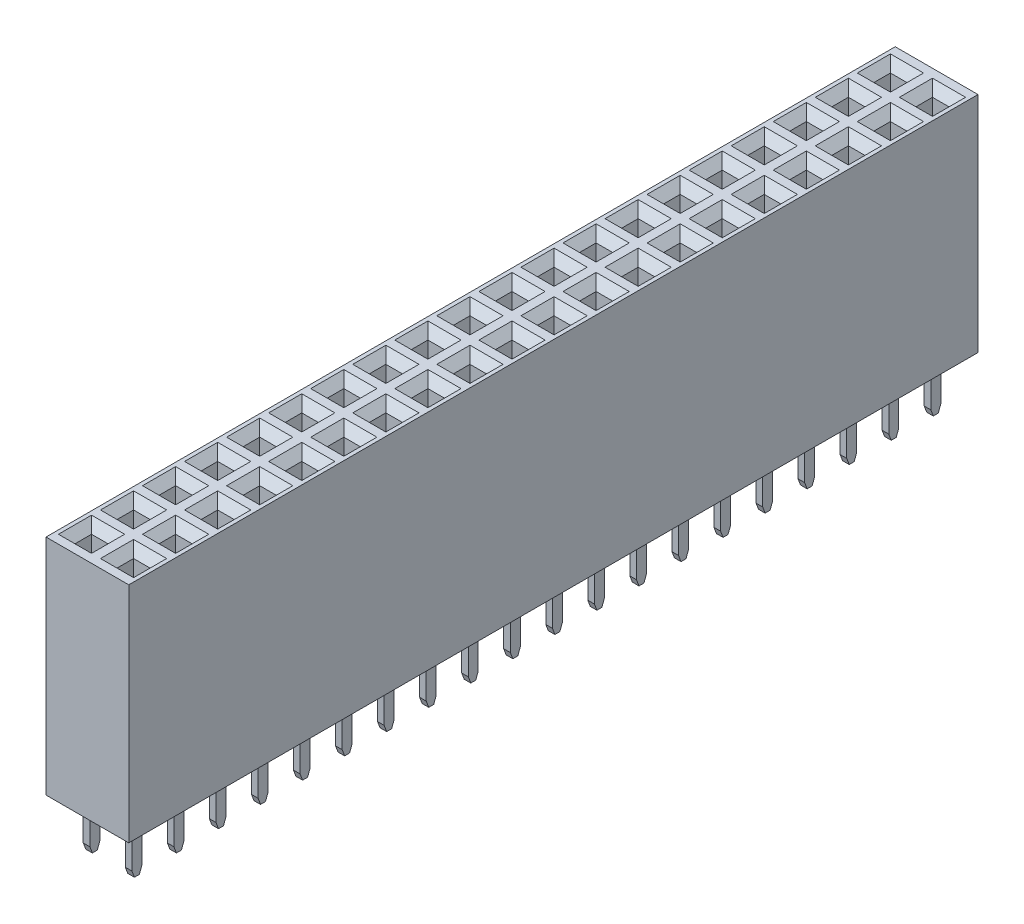
SolidWorks part; units mm, degrees
ref_plane "Спереди" through (0, 0, 0) normal (0, 0, 1) x (1, 0, 0)
ref_plane "Сверху" through (0, 0, 0) normal (0, 1, 0) x (1, 0, 0)
ref_plane "Справа" through (0, 0, 0) normal (1, 0, 0) x (0, 0, -1)
sketch "Эскиз1" plane through (0, 0, 0) normal (0, 0, 1) x (1, 0, 0)
  line L1 (-2.5, 13.5) -> (2.5, 13.5)
  line L2 (-2.5, 13.5) -> (-2.5, 0)
  line L3 (-2.5, 0) -> (2.5, 0)
  line L4 (2.5, 13.5) -> (2.5, 0)
  point P4 (0, 0)
  dimension "D1" = 13.5
  dimension "D2" = 5
extrude "Бобышка-Вытянуть1" add sketch "Эскиз1" along normal mid plane 51.3
sketch "Эскиз2" plane through (0, 13.5, 0) normal (0, 1, 0) x (1, 0, 0)
  line L0 (2.5, -25.65) -> (-2.5, -25.65) construction
  line L1 (-1.77, -24.63) -> (-0.77, -24.63)
  line L2 (-1.77, -24.63) -> (-1.77, -23.63)
  line L3 (-1.77, -23.63) -> (-0.77, -23.63)
  line L4 (-0.77, -24.63) -> (-0.77, -23.63)
  point P4 (-0.77, -24.13)
  point P7 (-1.27, -24.63)
  point P8 (0, -25.65)
  dimension "D1" = 1
  dimension "D2" = 1
  dimension "D3" = 1.52
  dimension "D4" = 1.27
extrude "Вырез-Вытянуть1" cut sketch "Эскиз2" against normal up to surface (13.5 mm away) up to face at (0, 0, 0)
chamfer "Фаска1" distance 0.5 angle 45 4 edges at (-0.77, 13.5, 24.13) (-1.27, 13.5, 24.63) (-1.77, 13.5, 24.13) (-1.27, 13.5, 23.63)
pattern_linear "Линейный массив1" count 20 spacing 2.54 along (0, 0, -1) count 2 spacing 2.54 along (1, 0, 0) of "Фаска1", "Вырез-Вытянуть1"
ref_plane "Плоскость4" through (-1.27, 0, 0) normal (1, 0, 0) x (0, 0, -1)
sketch "Эскиз3" plane through (-1.27, 0, 0) normal (1, 0, 0) x (0, 0, -1)
  line L0 (-23.83, 2) -> (-23.83, -2.6)
  line L1 (-23.83, -2.6) -> (-23.98, -3)
  line L2 (-23.98, -3) -> (-24.28, -3)
  line L3 (-24.28, -3) -> (-24.43, -2.6)
  line L4 (-24.43, -2.6) -> (-24.43, 2)
  line L5 (-24.43, 2) -> (-23.83, 2)
  line L6 (-24.63, 0) -> (-23.63, 0) construction
  line L7 (-25.65, 0) -> (25.65, 0) construction
  point P10 (-24.13, 2)
  point P11 (-24.13, 0)
  point P12 (0, 0)
  point P13 (-24.2831, -3)
  point P14 (-24.13, -3)
  dimension "D1" = 2
  dimension "D2" = 0.6
  dimension "D3" = 3
  dimension "D4" = 0.4
  dimension "D5" = 0.3
extrude "Бобышка-Вытянуть2" add sketch "Эскиз3" along normal mid plane 0.4 separate body
pattern_linear "Линейный массив2" count 20 spacing 2.54 along (0, 0, -1) count 2 spacing 2.54 along (1, 0, 0) of "Бобышка-Вытянуть2"
